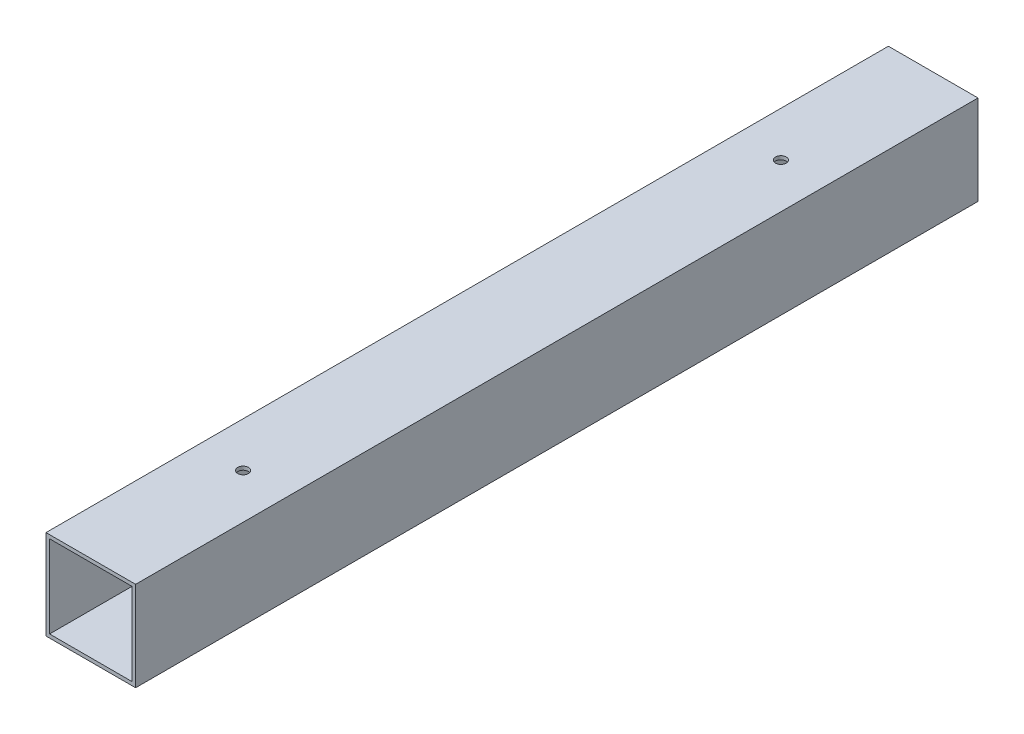
SolidWorks part; units mm, degrees
ref_plane "Front Plane" through (0, 0, 0) normal (0, 0, 1) x (1, 0, 0)
ref_plane "Top Plane" through (0, 0, 0) normal (0, 1, 0) x (1, 0, 0)
ref_plane "Right Plane" through (0, 0, 0) normal (1, 0, 0) x (0, 0, -1)
sketch "Sketch1" plane through (0, 0, 0) normal (0, 0, 1) x (1, 0, 0)
  line L0 (-11.5, 11.5) -> (11.5, 11.5)
  line L1 (-12.5, -12.5) -> (12.5, -12.5)
  line L2 (-12.5, -12.5) -> (-12.5, 12.5)
  line L3 (-12.5, 12.5) -> (12.5, 12.5)
  line L4 (12.5, -12.5) -> (12.5, 12.5)
  line L5 (-12.5, -12.5) -> (12.5, 12.5) construction
  line L6 (-12.5, 12.5) -> (12.5, -12.5) construction
  line L7 (11.5, -11.5) -> (11.5, 11.5)
  line L8 (-11.5, -11.5) -> (11.5, -11.5)
  line L9 (-11.5, -11.5) -> (-11.5, 11.5)
  point P0 (0, 0)
  dimension "D1" = 25
  dimension "D2" = 1
extrude "Boss-Extrude1" add sketch "Sketch1" along normal mid plane 235
sketch "Sketch2" plane through (0, 12.5, 0) normal (0, 1, 0) x (1, 0, 0)
  line L0 (0, -75) -> (0, 75) construction
  circle A0 centre (0, 75) radius 1.5
  circle A1 centre (0, -75) radius 1.5
  point P4 (0, 0)
  dimension "D2" = 3
  dimension "D1" = 150
extrude "Cut-Extrude1" cut sketch "Sketch2" against normal through all both and the other way through all
